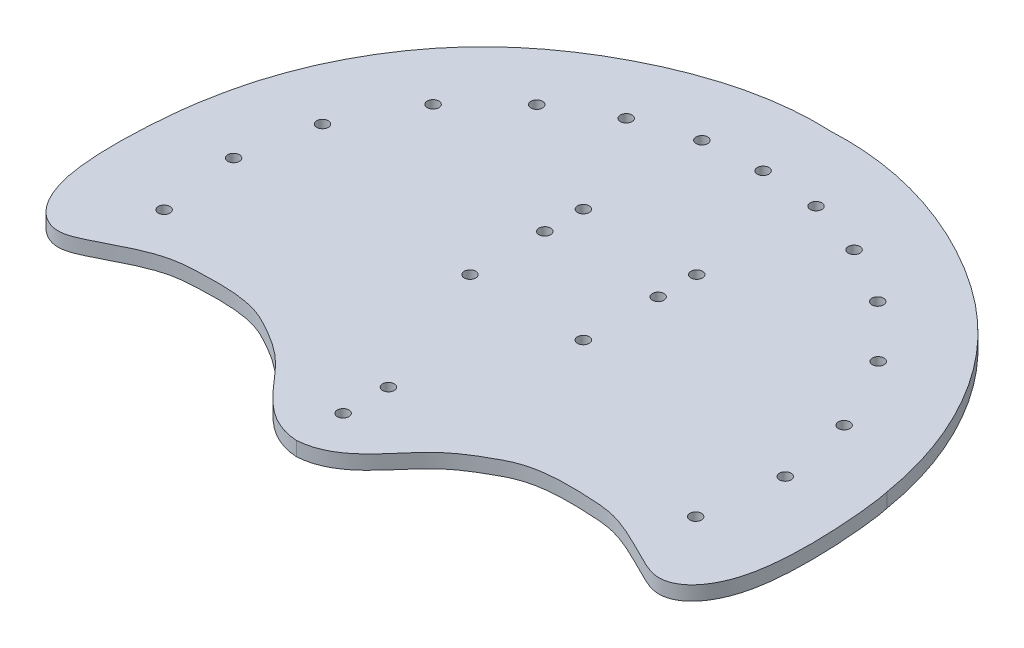
SolidWorks part; units mm, degrees
material "6061-T6 (SS)"
ref_plane "Front Plane" through (0, 0, 0) normal (0, 0, 1) x (1, 0, 0)
ref_plane "Top Plane" through (0, 0, 0) normal (0, 1, 0) x (1, 0, 0)
ref_plane "Right Plane" through (0, 0, 0) normal (1, 0, 0) x (0, 0, -1)
sketch "Sketch3" plane through (0, 0, 0) normal (0, 1, 0) x (1, 0, 0)
  line L0 (0, 0) -> (0, 159.1899) construction
  line L1 (0, 0) -> (0, -140.5301) construction
  line L2 (0, 0) -> (-190.5, 0) construction
  line L3 (0, 0) -> (190.5, 0) construction
  spline S0 degree 3 poles (-190.5, 0) (-184.3927, 37.537) (-157.2613, 93.9641) (-82.3875, 146.6227) (-31.3114, 160.7999) (0, 159.1899) knots 0 0 0 0 0.424401 0.65637 1 1 1 1
  spline S1 degree 3 poles (-190.5, 0) (-192.064, -4.9635) (-201.9672, -83.3146) (-174.6966, -109.29) (-151.6301, -100.568) (-131.4108, -87.7198) (-96.8436, -85.3754) (-78.6925, -86.2588) (-58.8335, -96.8794) (-37.3059, -109.9358) (-21.3496, -139.1148) (0, -140.5301) knots 0 0 0 0 0.166997 0.292321 0.319633 0.426735 0.458914 0.609242 0.64191 0.766802 1 1 1 1
  spline S2 degree 3 poles (190.5, 0) (192.064, -4.9635) (201.9672, -83.3146) (174.6966, -109.29) (151.6301, -100.568) (131.4108, -87.7198) (96.8436, -85.3754) (78.6925, -86.2588) (58.8335, -96.8794) (37.3059, -109.9358) (21.3496, -139.1148) (0, -140.5301) knots 0 0 0 0 0.166997 0.292321 0.319633 0.426735 0.458914 0.609242 0.64191 0.766802 1 1 1 1
  spline S3 degree 3 poles (190.5, 0) (184.3927, 37.537) (157.2613, 93.9641) (82.3875, 146.6227) (31.3114, 160.7999) (0, 159.1899) knots 0 0 0 0 0.424401 0.65637 1 1 1 1
  dimension "D1" = 381
  dimension "D2" = 299.72
  dimension "D3" = 159.1899
  dimension "D4" = 86.8953
  dimension "D5" = 104.4979
  dimension "D6" = 29.1616
  dimension "D7" = 92.2742
  dimension "D8" = 108.411
  dimension "D9" = 67.4883
  dimension "D10" = 43.7314
  dimension "D11" = 117.6915
  dimension "D12" = 162.2568
  dimension "D13" = 89.4522
  dimension "D14" = 140.1036
  dimension "D15" = 175.0666
  dimension "D16" = 50.2669
  dimension "D17" = 101.3666
  dimension "D18" = 138.1225
  dimension "D19" = 155.1557
  dimension "D20" = 192.0074
  dimension "D21" = 193.9268
  dimension "D23" = 76.6666
extrude "Boss-Extrude1" add sketch "Sketch3" along normal blind 7.9502 from surface at 0 starting at plane "Top Plane"
sketch "Sketch5" plane through (0, 0, 0) normal (0, -1, 0) x (1, 0, 0)
  line L0 (0, 0) -> (0, -20.32) construction
  line L1 (31.75, -52.07) -> (-31.75, -52.07)
  line L2 (31.75, -52.07) -> (31.75, 11.43)
  line L3 (31.75, 11.43) -> (-31.75, 11.43)
  line L4 (-31.75, -52.07) -> (-31.75, 11.43)
  line L5 (31.75, -52.07) -> (-31.75, 11.43) construction
  line L6 (31.75, 11.43) -> (-31.75, -52.07) construction
  line L7 (-31.75, -52.07) -> (-31.75, -30.48)
  line L8 (-31.75, -30.48) -> (31.75, -30.48) construction
  line L9 (0, -20.32) -> (140.7253, -20.32) construction
  line L10 (0, -20.32) -> (0, -97.1287) construction
  line L11 (0, -20.32) -> (31.9753, -118.7297) construction
  line L13 (0, -20.32) -> (63.8443, -108.1942) construction
  line L14 (0, -20.32) -> (95.5392, -89.7333) construction
  line L15 (124.7166, -60.8429) -> (0, -20.32) construction
  line L16 (0, -20.32) -> (154.5508, 21.0918) construction
  line L17 (0, -20.32) -> (148.922, 65.6601) construction
  line L18 (0, -20.32) -> (-31.9753, -118.7297) construction
  line L19 (0, -20.32) -> (-63.8443, -108.1942) construction
  line L20 (0, -20.32) -> (-95.5392, -89.7333) construction
  line L21 (-124.7166, -60.8429) -> (0, -20.32) construction
  line L22 (0, -20.32) -> (-154.5508, 21.0918) construction
  line L23 (0, -20.32) -> (-148.922, 65.6601) construction
  spline S0 degree 3 poles (-148.922, 65.6601) (-157.8584, 40.2253) (-156.2837, 8.5854) (-143.1202, -28.9506) (-139.3242, -37.3463) (-130.3709, -53.1962) (-125.215, -60.649) (-118.0488, -69.1403) (-116.5795, -70.7975) (-113.5719, -74.0252) (-112.0368, -75.592) (-107.2801, -80.2116) (-103.9215, -83.1695) (-93.3361, -91.6595) (-85.5959, -96.8074) (-76.3408, -101.9556) (-75.3049, -102.5187) (-73.219, -103.6268) (-72.1677, -104.1726) (-69.0049, -105.7765) (-66.8862, -106.8006) (-60.5068, -109.7299) (-56.2231, -111.4921) (-47.6308, -114.6027) (-43.3223, -115.9511) (-34.7104, -118.209) (-30.4072, -119.1185) (-21.8242, -120.4791) (-17.5446, -120.9304) (-11.1443, -121.2499) (-9.0138, -121.2968) (-5.8216, -121.2757) (-4.1848, -121.2414) (-2.5489, -121.1705) (-1.9677, -121.1408) (-1.9605, -121.1404) (-1.2995, -121.1064) (-0.6497, -121.073) (0, -121.0396) knots -0.292878 -0.292878 -0.292878 -0.292878 0.125 0.125 0.25 0.25 0.375 0.375 0.40625 0.40625 0.4375 0.4375 0.5 0.5 0.625 0.625 0.640625 0.640625 0.65625 0.65625 0.6875 0.6875 0.75 0.75 0.8125 0.8125 0.875 0.875 0.9375 0.9375 0.96875 0.96875 0.984375 0.992798 0.992798 0.99292 0.99292 1 1 1 1
  spline S5 degree 3 poles (998.6789, -69.6893) (665.1581, -86.8384) (331.6156, -103.9885) (-1.9268, -121.1387) (-1.9605, -121.1404) (-1.9677, -121.1408) (-2.5489, -121.1705) (-4.1848, -121.2414) (-5.8216, -121.2757) (-9.0138, -121.2968) (-11.1443, -121.2499) (-17.5446, -120.9304) (-21.8242, -120.4791) (-30.4072, -119.1185) (-34.7104, -118.209) (-43.3223, -115.9511) (-47.6308, -114.6027) (-56.2231, -111.4921) (-60.5068, -109.7299) (-66.8862, -106.8006) (-69.0049, -105.7765) (-72.1677, -104.1726) (-73.219, -103.6268) (-75.3049, -102.5187) (-76.3408, -101.9556) (-85.5959, -96.8074) (-93.3361, -91.6595) (-103.9215, -83.1695) (-107.2801, -80.2116) (-112.0368, -75.592) (-113.5719, -74.0252) (-116.5795, -70.7975) (-118.0488, -69.1403) (-125.215, -60.649) (-130.3709, -53.1962) (-139.3242, -37.3463) (-143.1202, -28.9506) (-198.5095, 128.9933) (-22.362, 351.6373) (651.8169, -587.5188) knots -3.627409 -3.627409 -3.627409 -3.627409 0.006836 0.00708 0.00708 0.007202 0.007202 0.015625 0.03125 0.03125 0.0625 0.0625 0.125 0.125 0.1875 0.1875 0.25 0.25 0.3125 0.3125 0.34375 0.34375 0.359375 0.359375 0.375 0.375 0.5 0.5 0.5625 0.5625 0.59375 0.59375 0.625 0.625 0.75 0.75 0.875 0.875 3.034324 3.034324 3.034324 3.034324 only from (0, -121.0396) to (-152.8945, 6.1184)
  spline S6 degree 3 poles (-1687.8289, -2297.0686) (-150.4269, 537.0593) (218.9922, 187.4002) (143.1202, -28.9506) (139.3242, -37.3463) (130.3709, -53.1962) (125.215, -60.649) (118.0488, -69.1403) (116.5795, -70.7975) (113.5719, -74.0252) (112.0368, -75.592) (107.2801, -80.2116) (103.9215, -83.1695) (93.3361, -91.6595) (85.5959, -96.8074) (76.3408, -101.9556) (75.3049, -102.5187) (73.219, -103.6268) (72.1677, -104.1726) (69.0049, -105.7765) (66.8862, -106.8006) (60.5068, -109.7299) (56.2231, -111.4921) (47.6308, -114.6027) (43.3223, -115.9511) (34.7104, -118.209) (30.4072, -119.1185) (21.8242, -120.4791) (17.5446, -120.9304) (11.1443, -121.2499) (9.0138, -121.2968) (5.8216, -121.2757) (4.1848, -121.2414) (2.5489, -121.1705) (1.9677, -121.1408) (1.9605, -121.1404) (-997.3522, -69.7575) (-1996.6535, -18.3753) (-2996.029, 33.0152) knots -2.879056 -2.879056 -2.879056 -2.879056 0.125 0.125 0.25 0.25 0.375 0.375 0.40625 0.40625 0.4375 0.4375 0.5 0.5 0.625 0.625 0.640625 0.640625 0.65625 0.65625 0.6875 0.6875 0.75 0.75 0.8125 0.8125 0.875 0.875 0.9375 0.9375 0.96875 0.96875 0.984375 0.992798 0.992798 0.99292 0.99292 11.881939 11.881939 11.881939 11.881939 only from (152.8945, 6.1184) to (0, -121.0396)
  spline S8 degree 3 poles (148.922, 65.6601) (157.8584, 40.2253) (156.2837, 8.5854) (143.1202, -28.9506) (139.3242, -37.3463) (130.3709, -53.1962) (125.215, -60.649) (118.0488, -69.1403) (116.5795, -70.7975) (113.5719, -74.0252) (112.0368, -75.592) (107.2801, -80.2116) (103.9215, -83.1695) (93.3361, -91.6595) (85.5959, -96.8074) (76.3408, -101.9556) (75.3049, -102.5187) (73.219, -103.6268) (72.1677, -104.1726) (69.0049, -105.7765) (66.8862, -106.8006) (60.5068, -109.7299) (56.2231, -111.4921) (47.6308, -114.6027) (43.3223, -115.9511) (34.7104, -118.209) (30.4072, -119.1185) (21.8242, -120.4791) (17.5446, -120.9304) (11.1443, -121.2499) (9.0138, -121.2968) (5.8216, -121.2757) (4.1848, -121.2414) (2.5489, -121.1705) (1.9677, -121.1408) (1.9605, -121.1404) (1.2995, -121.1064) (0.6497, -121.073) (0, -121.0396) knots -0.292878 -0.292878 -0.292878 -0.292878 0.125 0.125 0.25 0.25 0.375 0.375 0.40625 0.40625 0.4375 0.4375 0.5 0.5 0.625 0.625 0.640625 0.640625 0.65625 0.65625 0.6875 0.6875 0.75 0.75 0.8125 0.8125 0.875 0.875 0.9375 0.9375 0.96875 0.96875 0.984375 0.992798 0.992798 0.99292 0.99292 1 1 1 1
  point P0 (0, -20.32)
  point P3 (0, -20.32)
  point P14 (0, 114.3)
  point P16 (0, 88.9)
  dimension "D2" = 63.5
  dimension "D3" = 63.5
  dimension "D4" = 21.59
  dimension "D6" = 25.4
  dimension "D7" = 88.9
  dimension "D8" = 18
  dimension "D9" = 18
  dimension "D10" = 18
  dimension "D11" = 18
  dimension "D12" = 15
  dimension "D13" = 15
  dimension "D5" = 38.1
hole_wizard "F (0.257) Diameter Hole2" positions "Sketch6" profile "Sketch7" hole size "F" standard "ANSI Inch" end condition through all
sketch "Sketch6" plane through (0, 0, 0) normal (0, -1, 0) x (-1, 0, 0)
  line L0 (200000, 20.32) -> (-200140.7253, 20.32) construction
  spline S0 degree 3 poles (-148.922, -65.6601) (-157.8584, -40.2253) (-156.2837, -8.5854) (-143.1202, 28.9506) (-139.3242, 37.3463) (-130.3709, 53.1962) (-125.215, 60.649) (-118.0488, 69.1403) (-116.5795, 70.7975) (-113.5719, 74.0252) (-112.0368, 75.592) (-107.2801, 80.2116) (-103.9215, 83.1695) (-93.3361, 91.6595) (-85.5959, 96.8074) (-76.3408, 101.9556) (-75.3049, 102.5187) (-73.219, 103.6268) (-72.1677, 104.1726) (-69.0049, 105.7765) (-66.8862, 106.8006) (-60.5068, 109.7299) (-56.2231, 111.4921) (-47.6308, 114.6027) (-43.3223, 115.9511) (-34.7104, 118.209) (-30.4072, 119.1185) (-21.8242, 120.4791) (-17.5446, 120.9304) (-11.1443, 121.2499) (-9.0138, 121.2968) (-5.8216, 121.2757) (-4.1848, 121.2414) (-2.5489, 121.1705) (-1.9677, 121.1408) (-1.9605, 121.1404) (-1.2995, 121.1064) (-0.6497, 121.073) (0, 121.0396) knots -0.292878 -0.292878 -0.292878 -0.292878 0.125 0.125 0.25 0.25 0.375 0.375 0.40625 0.40625 0.4375 0.4375 0.5 0.5 0.625 0.625 0.640625 0.640625 0.65625 0.65625 0.6875 0.6875 0.75 0.75 0.8125 0.8125 0.875 0.875 0.9375 0.9375 0.96875 0.96875 0.984375 0.992798 0.992798 0.99292 0.99292 1 1 1 1 construction
  spline S1 degree 3 poles (148.922, -65.6601) (157.8584, -40.2253) (156.2837, -8.5854) (143.1202, 28.9506) (139.3242, 37.3463) (130.3709, 53.1962) (125.215, 60.649) (118.0488, 69.1403) (116.5795, 70.7975) (113.5719, 74.0252) (112.0368, 75.592) (107.2801, 80.2116) (103.9215, 83.1695) (93.3361, 91.6595) (85.5959, 96.8074) (76.3408, 101.9556) (75.3049, 102.5187) (73.219, 103.6268) (72.1677, 104.1726) (69.0049, 105.7765) (66.8862, 106.8006) (60.5068, 109.7299) (56.2231, 111.4921) (47.6308, 114.6027) (43.3223, 115.9511) (34.7104, 118.209) (30.4072, 119.1185) (21.8242, 120.4791) (17.5446, 120.9304) (11.1443, 121.2499) (9.0138, 121.2968) (5.8216, 121.2757) (4.1848, 121.2414) (2.5489, 121.1705) (1.9677, 121.1408) (1.9605, 121.1404) (1.2995, 121.1064) (0.6497, 121.073) (0, 121.0396) knots -0.292878 -0.292878 -0.292878 -0.292878 0.125 0.125 0.25 0.25 0.375 0.375 0.40625 0.40625 0.4375 0.4375 0.5 0.5 0.625 0.625 0.640625 0.640625 0.65625 0.65625 0.6875 0.6875 0.75 0.75 0.8125 0.8125 0.875 0.875 0.9375 0.9375 0.96875 0.96875 0.984375 0.992798 0.992798 0.99292 0.99292 1 1 1 1 construction
  point P3 (31.75, 52.07)
  point P6 (31.75, -11.43)
  point P9 (-31.75, -11.43)
  point P15 (31.75, 30.48)
  point P32 (-31.75, 30.48)
  point P39 (-31.75, 52.07)
  point P42 (-154.5508, -21.0918)
  point P45 (-148.922, -65.6601)
  point P48 (-146.1469, 20.32)
  point P54 (-124.7166, 60.8429)
  point P57 (-95.5392, 89.7333)
  point P60 (148.922, -65.6601)
  point P63 (154.5508, -21.0918)
  point P66 (124.7166, 60.8429)
  point P69 (95.5392, 89.7333)
  point P72 (63.8443, 108.1942)
  point P76 (31.9753, 118.7297)
  point P79 (0, 121.0396)
  point P82 (-31.9753, 118.7297)
  point P85 (-63.8443, 108.1942)
  point P88 (-95.5392, 89.7333)
  point P91 (146.1469, 20.32)
  point P95 (0, -88.9)
  point P98 (0, -114.3)
sketch "Sketch7" plane through (-31.75, 0, -52.07) normal (1, 0, 0) x (0, 0, -1)
  line L0 (0, 0) -> (0, 7.9502)
  line L1 (0, 7.9502) -> (3.2639, 7.9502)
  line L2 (3.2639, 7.9502) -> (3.2639, 0)
  line L5 (3.2639, 0) -> (0, 0)
  line L11 (0, -6.35) -> (0, 107.95) construction
  dimension "Thru Hole Dia." = 6.5278
  dimension "Thru Hole Depth" = 7.9502
sketch "Sketch9" [suppressed] plane through (0, 7.9502, 0) normal (0, 1, 0) x (1, 0, 0)
  line L0 (102.3823, -86.0787) -> (102.3823, 130.9193)
  line L1 (-50.7649, -102.4301) -> (50.7649, -102.4301)
  spline S0 degree 3 poles (0, -140.5301) (21.3496, -139.1148) (37.3059, -109.9358) (58.8335, -96.8794) (78.6925, -86.2588) (96.8436, -85.3754) (131.4108, -87.7198) (151.6301, -100.568) (174.6966, -109.29) (201.9672, -83.3146) (192.064, -4.9635) (190.5, 0) knots 0 0 0 0 0.233198 0.35809 0.390758 0.541086 0.573265 0.680367 0.707679 0.833003 1 1 1 1 construction
  spline S1 degree 3 poles (190.5, 0) (184.3927, 37.537) (157.2613, 93.9641) (82.3875, 146.6227) (31.3114, 160.7999) (0, 159.1899) knots 0 0 0 0 0.424401 0.65637 1 1 1 1 construction
  spline S2 degree 3 poles (-190.5, 0) (-192.064, -4.9635) (-201.9672, -83.3146) (-174.6966, -109.29) (-151.6301, -100.568) (-131.4108, -87.7198) (-96.8436, -85.3754) (-78.6925, -86.2588) (-58.8335, -96.8794) (-37.3059, -109.9358) (-21.3496, -139.1148) (0, -140.5301) knots 0 0 0 0 0.166997 0.292321 0.319633 0.426735 0.458914 0.609242 0.64191 0.766802 1 1 1 1 construction
  dimension "D1" = 38.1
split line "Split Line1" [suppressed]
equation "\"Plate thickness\"=0.313"
equation "\"D1@Boss-Extrude1\"=\"Plate thickness\""
equation "\"Bracket Alignment\"= .80"
equation "\"D1@Sketch5\"=\"Bracket Alignment\""
